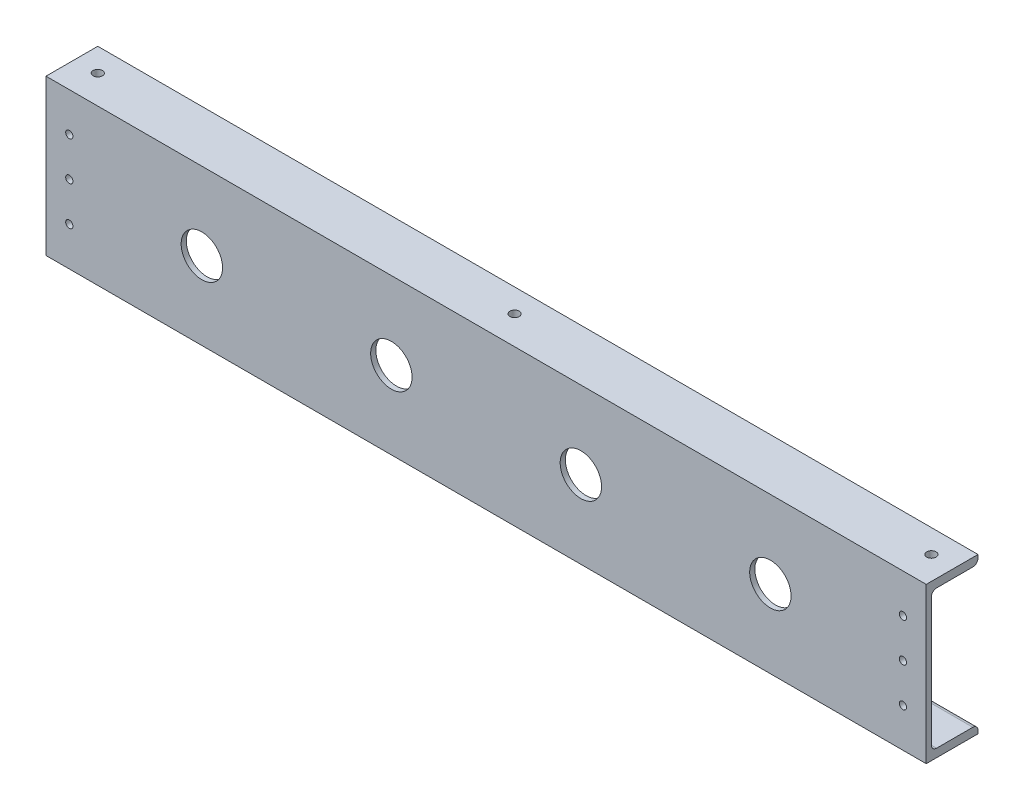
SolidWorks part; units mm, degrees
material "ASTM A36 Steel"
ref_plane "Front Plane" through (0, 0, 0) normal (0, 0, 1) x (1, 0, 0)
ref_plane "Top Plane" through (0, 0, 0) normal (0, 1, 0) x (1, 0, 0)
ref_plane "Right Plane" through (0, 0, 0) normal (1, 0, 0) x (0, 0, -1)
sketch "Sketch1" plane through (0, 0, 0) normal (1, 0, 0) x (0, 0, -1)
  line L0 (-86.6221, 113.8796) -> (-186.6221, 113.8796)
  line L1 (-186.6221, 113.8796) -> (-186.6221, -186.1204)
  line L2 (-186.6221, -186.1204) -> (-86.6221, -186.1204)
  line L3 (-86.6221, -186.1204) -> (-86.6221, -180.1204)
  line L4 (-96.6221, -170.1204) -> (-166.6221, -170.1204)
  line L5 (-176.6221, -160.1204) -> (-176.6221, 87.8796)
  line L6 (-166.6221, 97.8796) -> (-96.6221, 97.8796)
  line L7 (-86.6221, 107.8796) -> (-86.6221, 113.8796)
  arc A0 (-166.6221, -170.1204) -> (-176.6221, -160.1204) centre (-166.6221, -160.1204) cw
  arc A1 (-86.6221, -180.1204) -> (-96.6221, -170.1204) centre (-96.6221, -180.1204) ccw
  arc A2 (-96.6221, 97.8796) -> (-86.6221, 107.8796) centre (-96.6221, 107.8796) ccw
  arc A3 (-176.6221, 87.8796) -> (-166.6221, 97.8796) centre (-166.6221, 87.8796) cw
  point P12 (-86.6221, -170.1204)
  point P15 (-86.6221, 97.8796)
  dimension "D7" = 10
  dimension "D1" = 300
  dimension "D2" = 100
  dimension "D3" = 100
  dimension "D4" = 10
  dimension "D5" = 16
  dimension "D6" = 16
extrude "Boss-Extrude1" add sketch "Sketch1" along normal blind 1700
sketch "Sketch3" plane through (0, 0, 186.6221) normal (0, 0, 1) x (1, 0, 0)
  line L0 (1700, 113.8796) -> (0, 113.8796) construction
  line L1 (1700, 113.8796) -> (1700, -186.1204) construction
  circle A0 centre (1655, 38.8796) radius 7
  circle A1 centre (1655, -36.1204) radius 7
  circle A2 centre (1655, -111.1204) radius 7
  dimension "D1" = 14
  dimension "D2" = 14
  dimension "D3" = 14
  dimension "D4" = 75
  dimension "D5" = 75
  dimension "D6" = 75
  dimension "D7" = 45
  dimension "D8" = 45
extrude "Cut-Extrude1" cut sketch "Sketch3" against normal blind 10
ref_plane "Plane1" through (850, 0, 0) normal (1, 0, 0) x (0, 0, -1)
mirror "Mirror1" about plane through (850, 0, 0) normal (1, 0, 0) of "Cut-Extrude1"
sketch "Sketch4" plane through (0, 113.8796, 0) normal (0, 1, 0) x (1, 0, 0)
  line L0 (1700, -86.6221) -> (0, -86.6221) construction
  line L1 (0, -86.6221) -> (0, -186.6221) construction
  circle A0 centre (45, -131.6221) radius 9
  dimension "D1" = 18
  dimension "D2" = 45
  dimension "D3" = 45
extrude "Cut-Extrude2" cut sketch "Sketch4" against normal blind 20
pattern_linear "LPattern1" count 3 spacing 805 along (1, 0, 0) of "Cut-Extrude2"
sketch "Sketch5" plane through (0, 0, 176.6221) normal (0, 0, -1) x (-1, 0, 0)
  line L0 (-1700, -160.1204) -> (-1700, 87.8796) construction
  line L1 (-1700, 113.8796) -> (0, 113.8796) construction
  circle A0 centre (-1399, -36.1204) radius 40
  dimension "D1" = 80
  dimension "D2" = 301
  dimension "D3" = 150
extrude "Cut-Extrude3" cut sketch "Sketch5" against normal blind 30
pattern_linear "LPattern2" count 4 spacing 366 along (-1, 0, 0) of "Cut-Extrude3"
